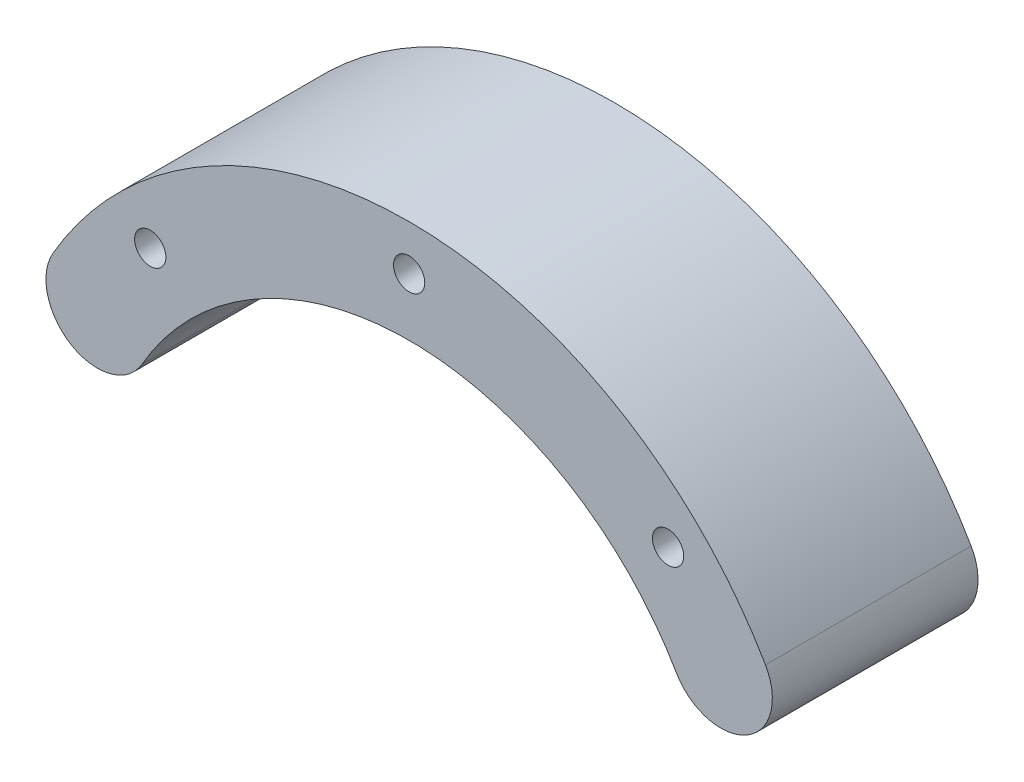
SolidWorks part; units mm, degrees
ref_plane "前视基准面" through (0, 0, 0) normal (0, 0, 1) x (1, 0, 0)
ref_plane "上视基准面" through (0, 0, 0) normal (0, 1, 0) x (1, 0, 0)
ref_plane "右视基准面" through (0, 0, 0) normal (1, 0, 0) x (0, 0, -1)
other "Configuration Table"
sketch "草图2" plane through (0, 0, 0) normal (0, 0, 1) x (1, 0, 0)
  line L0 (-21.7161, 24.1127) -> (16.1725, 2.2377) construction
  line L1 (16.1725, 2.2377) -> (-60.3112, 2.2377) construction
  line L2 (16.1725, 56.4636) -> (16.1725, -56.4636) construction
  arc A0 (48.6485, 20.9877) -> (-16.3034, 20.9877) centre (16.1725, 2.2377) ccw
  arc A1 (59.4738, 27.2377) -> (-27.1287, 27.2377) centre (16.1725, 2.2377) ccw
  arc A2 (56.7916, 18.4907) -> (16.1725, -41.5123) centre (16.1725, 2.2377) ccw construction
  arc A3 (-27.1287, 27.2377) -> (-16.3034, 20.9877) centre (-21.7161, 24.1127) ccw
  arc A4 (59.4738, 27.2377) -> (48.6485, 20.9877) centre (54.0612, 24.1127) cw
  circle A5 centre (-15.2937, 33.704) radius 1.9
  circle A6 centre (16.1725, 46.7377) radius 1.9
  circle A7 centre (47.6388, 33.704) radius 1.9
  dimension "D2" = 75
  dimension "D3" = 87.5
  dimension "D4" = 30
extrude "凸台-拉伸1" add sketch "草图2" along normal blind 25
